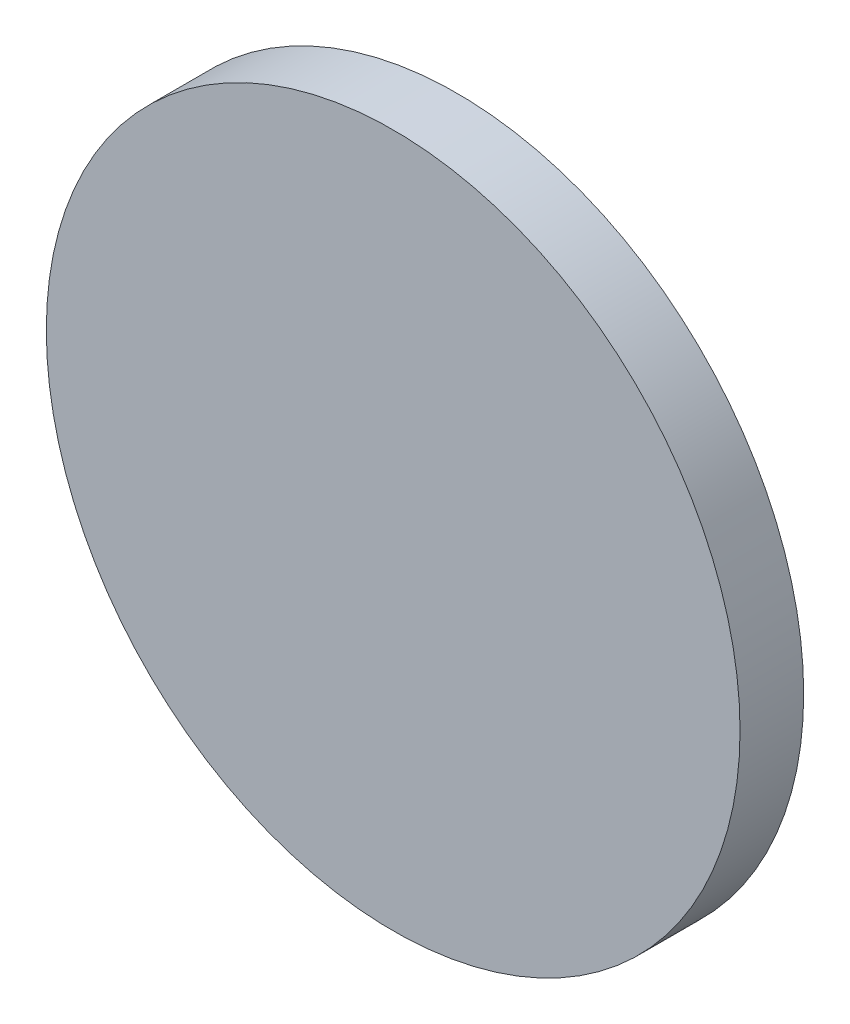
SolidWorks part; units mm, degrees
ref_plane "Alzado" through (0, 0, 0) normal (0, 0, 1) x (1, 0, 0)
ref_plane "Planta" through (0, 0, 0) normal (0, 1, 0) x (1, 0, 0)
ref_plane "Vista lateral" through (0, 0, 0) normal (1, 0, 0) x (0, 0, -1)
sketch "Boceto" plane through (0, 0, 0) normal (0, 0, 1) x (1, 0, 0)
  line L0 (0, 225) -> (-225, 225) construction
  line L1 (-225, 0) -> (-225, 225) construction
  line L2 (0, -225) -> (225, -225) construction
  line L3 (225, 0) -> (225, -225) construction
  line L4 (-225, 225) -> (225, -225) construction
  line L5 (-172.6866, 172.6866) -> (172.6866, 172.6866)
  line L6 (-192.6866, 192.6866) -> (192.6866, 192.6866)
  line L7 (-192.6866, 192.6866) -> (-192.6866, -192.6866)
  line L8 (-192.6866, -192.6866) -> (192.6866, -192.6866)
  line L9 (192.6866, 192.6866) -> (192.6866, -192.6866)
  line L10 (172.6866, 172.6866) -> (172.6866, -172.6866)
  line L11 (-172.6866, -172.6866) -> (172.6866, -172.6866)
  line L12 (-172.6866, 172.6866) -> (-172.6866, -172.6866)
  circle A0 centre (0, 0) radius 225
  circle A1 centre (0, 0) radius 272.5
  dimension "SafeDiameter" = 545
  dimension "DentroRobot" = 450
  dimension "D3" = 20
sketch "Sprite" plane through (0, 0, 0) normal (0, 0, 1) x (1, 0, 0)
  line L5 (-172.6866, 172.6866) -> (172.6866, 172.6866)
  line L6 (-192.6866, 192.6866) -> (192.6866, 192.6866)
  line L7 (-192.6866, 192.6866) -> (-192.6866, -192.6866)
  line L8 (-192.6866, -192.6866) -> (192.6866, -192.6866)
  line L9 (192.6866, 192.6866) -> (192.6866, -192.6866)
  line L10 (172.6866, 172.6866) -> (172.6866, -172.6866)
  line L11 (-172.6866, -172.6866) -> (172.6866, -172.6866)
  line L12 (-172.6866, 172.6866) -> (-172.6866, -172.6866)
  circle A0 centre (0, 0) radius 225
  circle A1 centre (0, 0) radius 272.5
  dimension "SafeDiameter" = 545
  dimension "DentroRobot" = 450
  dimension "D3" = 20
sketch "BaseRobot" plane through (0, 0, 0) normal (0, 0, 1) x (1, 0, 0)
  line L5 (-172.6866, 172.6866) -> (172.6866, 172.6866)
  line L6 (-192.6866, 192.6866) -> (192.6866, 192.6866)
  line L7 (-192.6866, 192.6866) -> (-192.6866, -192.6866)
  line L8 (-192.6866, -192.6866) -> (192.6866, -192.6866)
  line L9 (192.6866, 192.6866) -> (192.6866, -192.6866)
  line L10 (172.6866, 172.6866) -> (172.6866, -172.6866)
  line L11 (-172.6866, -172.6866) -> (172.6866, -172.6866)
  line L12 (-172.6866, 172.6866) -> (-172.6866, -172.6866)
  circle A0 centre (0, 0) radius 225
  circle A1 centre (0, 0) radius 272.5
  dimension "SafeDiameter" = 545
  dimension "DentroRobot" = 450
  dimension "D3" = 20
extrude "Base" add sketch "BaseRobot" along normal blind 50 contours A1
